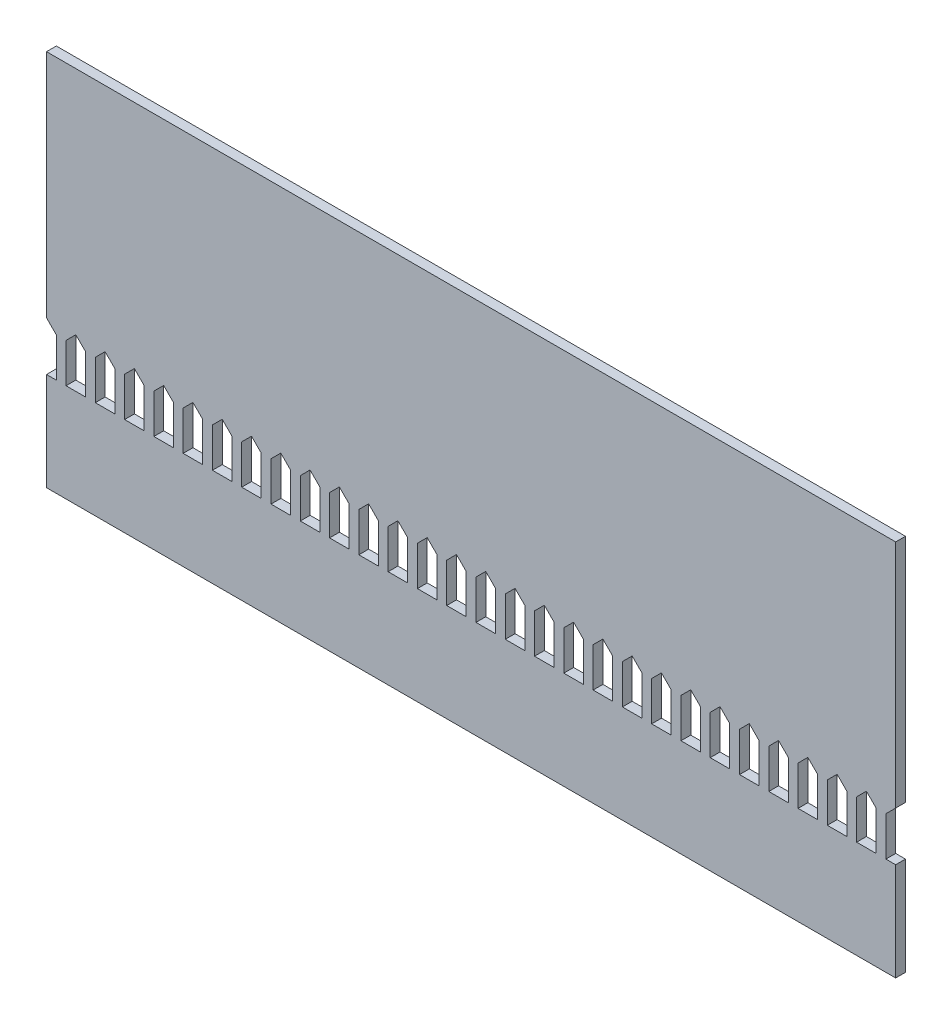
SolidWorks part; units mm, degrees
ref_plane "Front Plane" through (0, 0, 0) normal (0, 0, 1) x (1, 0, 0)
ref_plane "Top Plane" through (0, 0, 0) normal (0, 1, 0) x (1, 0, 0)
ref_plane "Right Plane" through (0, 0, 0) normal (1, 0, 0) x (0, 0, -1)
sketch "Sketch1" plane through (0, 0, 0) normal (0, 0, -1) x (1, 0, 0)
  line L1 (0, 0) -> (173.13, 0)
  line L3 (0, -47) -> (173.13, -47)
  line L5 (0, 30) -> (173.13, 30)
  line L7 (0, 0) -> (1.99, 1.99)
  line L8 (1.99, 1.99) -> (1.99, 10)
  line L9 (1.99, 10) -> (0, 10)
  line L10 (1.99, 5.995) -> (3.98, 5.995) construction
  line L11 (3.98, 1.99) -> (3.98, 10)
  line L12 (3.98, 1.99) -> (5.97, 0)
  line L13 (5.97, 0) -> (7.96, 1.99)
  line L14 (7.96, 1.99) -> (7.96, 10)
  line L15 (7.96, 10) -> (3.98, 10)
  line L16 (7.96, 1.99) -> (3.98, 1.99) construction
  line L17 (5.97, 0) -> (5.97, 1.99) construction
  line L23 (9.95, 1.99) -> (9.95, 10)
  line L44 (9.95, 1.99) -> (11.94, 0)
  line L65 (11.94, 0) -> (13.93, 1.99)
  line L86 (13.93, 1.99) -> (13.93, 10)
  line L107 (13.93, 10) -> (9.95, 10)
  line L128 (13.93, 1.99) -> (9.95, 1.99) construction
  line L149 (11.94, 0) -> (11.94, 1.99) construction
  line L170 (15.92, 1.99) -> (15.92, 10)
  line L191 (15.92, 1.99) -> (17.91, 0)
  line L207 (17.91, 0) -> (19.9, 1.99)
  line L213 (19.9, 1.99) -> (19.9, 10)
  line L219 (19.9, 10) -> (15.92, 10)
  line L225 (19.9, 1.99) -> (15.92, 1.99) construction
  line L231 (17.91, 0) -> (17.91, 1.99) construction
  line L237 (21.89, 1.99) -> (21.89, 10)
  line L243 (21.89, 1.99) -> (23.88, 0)
  line L249 (23.88, 0) -> (25.87, 1.99)
  line L255 (25.87, 1.99) -> (25.87, 10)
  line L261 (25.87, 10) -> (21.89, 10)
  line L267 (25.87, 1.99) -> (21.89, 1.99) construction
  line L273 (23.88, 0) -> (23.88, 1.99) construction
  line L279 (27.86, 1.99) -> (27.86, 10)
  line L285 (27.86, 1.99) -> (29.85, 0)
  line L291 (29.85, 0) -> (31.84, 1.99)
  line L297 (31.84, 1.99) -> (31.84, 10)
  line L303 (31.84, 10) -> (27.86, 10)
  line L309 (31.84, 1.99) -> (27.86, 1.99) construction
  line L315 (29.85, 0) -> (29.85, 1.99) construction
  line L316 (33.83, 1.99) -> (33.83, 10)
  line L317 (33.83, 1.99) -> (35.82, 0)
  line L318 (35.82, 0) -> (37.81, 1.99)
  line L319 (37.81, 1.99) -> (37.81, 10)
  line L320 (37.81, 10) -> (33.83, 10)
  line L321 (37.81, 1.99) -> (33.83, 1.99) construction
  line L322 (35.82, 0) -> (35.82, 1.99) construction
  line L323 (39.8, 1.99) -> (39.8, 10)
  line L324 (39.8, 1.99) -> (41.79, 0)
  line L325 (41.79, 0) -> (43.78, 1.99)
  line L326 (43.78, 1.99) -> (43.78, 10)
  line L327 (43.78, 10) -> (39.8, 10)
  line L328 (43.78, 1.99) -> (39.8, 1.99) construction
  line L329 (41.79, 0) -> (41.79, 1.99) construction
  line L330 (45.77, 1.99) -> (45.77, 10)
  line L331 (45.77, 1.99) -> (47.76, 0)
  line L332 (47.76, 0) -> (49.75, 1.99)
  line L333 (49.75, 1.99) -> (49.75, 10)
  line L334 (49.75, 10) -> (45.77, 10)
  line L335 (49.75, 1.99) -> (45.77, 1.99) construction
  line L336 (47.76, 0) -> (47.76, 1.99) construction
  line L337 (51.74, 1.99) -> (51.74, 10)
  line L338 (51.74, 1.99) -> (53.73, 0)
  line L339 (53.73, 0) -> (55.72, 1.99)
  line L340 (55.72, 1.99) -> (55.72, 10)
  line L341 (55.72, 10) -> (51.74, 10)
  line L342 (55.72, 1.99) -> (51.74, 1.99) construction
  line L343 (53.73, 0) -> (53.73, 1.99) construction
  line L344 (57.71, 1.99) -> (57.71, 10)
  line L345 (57.71, 1.99) -> (59.7, 0)
  line L346 (59.7, 0) -> (61.69, 1.99)
  line L347 (61.69, 1.99) -> (61.69, 10)
  line L348 (61.69, 10) -> (57.71, 10)
  line L349 (61.69, 1.99) -> (57.71, 1.99) construction
  line L350 (59.7, 0) -> (59.7, 1.99) construction
  line L351 (63.68, 1.99) -> (63.68, 10)
  line L352 (63.68, 1.99) -> (65.67, 0)
  line L353 (65.67, 0) -> (67.66, 1.99)
  line L354 (67.66, 1.99) -> (67.66, 10)
  line L355 (67.66, 10) -> (63.68, 10)
  line L356 (67.66, 1.99) -> (63.68, 1.99) construction
  line L357 (65.67, 0) -> (65.67, 1.99) construction
  line L358 (69.65, 1.99) -> (69.65, 10)
  line L359 (69.65, 1.99) -> (71.64, 0)
  line L360 (71.64, 0) -> (73.63, 1.99)
  line L361 (73.63, 1.99) -> (73.63, 10)
  line L362 (73.63, 10) -> (69.65, 10)
  line L363 (73.63, 1.99) -> (69.65, 1.99) construction
  line L364 (71.64, 0) -> (71.64, 1.99) construction
  line L365 (75.62, 1.99) -> (75.62, 10)
  line L366 (75.62, 1.99) -> (77.61, 0)
  line L367 (77.61, 0) -> (79.6, 1.99)
  line L368 (79.6, 1.99) -> (79.6, 10)
  line L369 (79.6, 10) -> (75.62, 10)
  line L370 (79.6, 1.99) -> (75.62, 1.99) construction
  line L371 (77.61, 0) -> (77.61, 1.99) construction
  line L372 (81.59, 1.99) -> (81.59, 10)
  line L373 (81.59, 1.99) -> (83.58, 0)
  line L374 (83.58, 0) -> (85.57, 1.99)
  line L375 (85.57, 1.99) -> (85.57, 10)
  line L376 (85.57, 10) -> (81.59, 10)
  line L377 (85.57, 1.99) -> (81.59, 1.99) construction
  line L378 (83.58, 0) -> (83.58, 1.99) construction
  line L379 (87.56, 1.99) -> (87.56, 10)
  line L380 (87.56, 1.99) -> (89.55, 0)
  line L381 (89.55, 0) -> (91.54, 1.99)
  line L382 (91.54, 1.99) -> (91.54, 10)
  line L383 (91.54, 10) -> (87.56, 10)
  line L384 (91.54, 1.99) -> (87.56, 1.99) construction
  line L385 (89.55, 0) -> (89.55, 1.99) construction
  line L386 (93.53, 1.99) -> (93.53, 10)
  line L387 (93.53, 1.99) -> (95.52, 0)
  line L388 (95.52, 0) -> (97.51, 1.99)
  line L389 (97.51, 1.99) -> (97.51, 10)
  line L390 (97.51, 10) -> (93.53, 10)
  line L391 (97.51, 1.99) -> (93.53, 1.99) construction
  line L392 (95.52, 0) -> (95.52, 1.99) construction
  line L393 (99.5, 1.99) -> (99.5, 10)
  line L394 (99.5, 1.99) -> (101.49, 0)
  line L395 (101.49, 0) -> (103.48, 1.99)
  line L396 (103.48, 1.99) -> (103.48, 10)
  line L397 (103.48, 10) -> (99.5, 10)
  line L398 (103.48, 1.99) -> (99.5, 1.99) construction
  line L399 (101.49, 0) -> (101.49, 1.99) construction
  line L400 (105.47, 1.99) -> (105.47, 10)
  line L401 (105.47, 1.99) -> (107.46, 0)
  line L402 (107.46, 0) -> (109.45, 1.99)
  line L403 (109.45, 1.99) -> (109.45, 10)
  line L404 (109.45, 10) -> (105.47, 10)
  line L405 (109.45, 1.99) -> (105.47, 1.99) construction
  line L406 (107.46, 0) -> (107.46, 1.99) construction
  line L407 (111.44, 1.99) -> (111.44, 10)
  line L408 (111.44, 1.99) -> (113.43, 0)
  line L409 (113.43, 0) -> (115.42, 1.99)
  line L410 (115.42, 1.99) -> (115.42, 10)
  line L411 (115.42, 10) -> (111.44, 10)
  line L412 (115.42, 1.99) -> (111.44, 1.99) construction
  line L413 (113.43, 0) -> (113.43, 1.99) construction
  line L414 (117.41, 1.99) -> (117.41, 10)
  line L415 (117.41, 1.99) -> (119.4, 0)
  line L416 (119.4, 0) -> (121.39, 1.99)
  line L417 (121.39, 1.99) -> (121.39, 10)
  line L418 (121.39, 10) -> (117.41, 10)
  line L419 (121.39, 1.99) -> (117.41, 1.99) construction
  line L420 (119.4, 0) -> (119.4, 1.99) construction
  line L421 (123.38, 1.99) -> (123.38, 10)
  line L422 (123.38, 1.99) -> (125.37, 0)
  line L423 (125.37, 0) -> (127.36, 1.99)
  line L424 (127.36, 1.99) -> (127.36, 10)
  line L425 (127.36, 10) -> (123.38, 10)
  line L426 (127.36, 1.99) -> (123.38, 1.99) construction
  line L427 (125.37, 0) -> (125.37, 1.99) construction
  line L428 (129.35, 1.99) -> (129.35, 10)
  line L429 (129.35, 1.99) -> (131.34, 0)
  line L430 (131.34, 0) -> (133.33, 1.99)
  line L431 (133.33, 1.99) -> (133.33, 10)
  line L432 (133.33, 10) -> (129.35, 10)
  line L433 (133.33, 1.99) -> (129.35, 1.99) construction
  line L434 (131.34, 0) -> (131.34, 1.99) construction
  line L435 (135.32, 1.99) -> (135.32, 10)
  line L436 (135.32, 1.99) -> (137.31, 0)
  line L437 (137.31, 0) -> (139.3, 1.99)
  line L438 (139.3, 1.99) -> (139.3, 10)
  line L439 (139.3, 10) -> (135.32, 10)
  line L440 (139.3, 1.99) -> (135.32, 1.99) construction
  line L441 (137.31, 0) -> (137.31, 1.99) construction
  line L442 (141.29, 1.99) -> (141.29, 10)
  line L443 (141.29, 1.99) -> (143.28, 0)
  line L444 (143.28, 0) -> (145.27, 1.99)
  line L445 (145.27, 1.99) -> (145.27, 10)
  line L446 (145.27, 10) -> (141.29, 10)
  line L447 (145.27, 1.99) -> (141.29, 1.99) construction
  line L448 (143.28, 0) -> (143.28, 1.99) construction
  line L449 (147.26, 1.99) -> (147.26, 10)
  line L450 (147.26, 1.99) -> (149.25, 0)
  line L451 (149.25, 0) -> (151.24, 1.99)
  line L452 (151.24, 1.99) -> (151.24, 10)
  line L453 (151.24, 10) -> (147.26, 10)
  line L454 (151.24, 1.99) -> (147.26, 1.99) construction
  line L455 (149.25, 0) -> (149.25, 1.99) construction
  line L456 (153.23, 1.99) -> (153.23, 10)
  line L457 (153.23, 1.99) -> (155.22, 0)
  line L458 (155.22, 0) -> (157.21, 1.99)
  line L459 (157.21, 1.99) -> (157.21, 10)
  line L460 (157.21, 10) -> (153.23, 10)
  line L461 (157.21, 1.99) -> (153.23, 1.99) construction
  line L462 (155.22, 0) -> (155.22, 1.99) construction
  line L463 (159.2, 1.99) -> (159.2, 10)
  line L464 (159.2, 1.99) -> (161.19, 0)
  line L465 (161.19, 0) -> (163.18, 1.99)
  line L466 (163.18, 1.99) -> (163.18, 10)
  line L467 (163.18, 10) -> (159.2, 10)
  line L468 (163.18, 1.99) -> (159.2, 1.99) construction
  line L469 (161.19, 0) -> (161.19, 1.99) construction
  line L470 (165.17, 1.99) -> (165.17, 10)
  line L471 (165.17, 1.99) -> (167.16, 0)
  line L472 (167.16, 0) -> (169.15, 1.99)
  line L473 (169.15, 1.99) -> (169.15, 10)
  line L474 (169.15, 10) -> (165.17, 10)
  line L475 (169.15, 1.99) -> (165.17, 1.99) construction
  line L476 (167.16, 0) -> (167.16, 1.99) construction
  line L477 (86.565, 30) -> (86.565, -47) construction
  line L478 (173.13, 0) -> (171.14, 1.99)
  line L479 (171.14, 1.99) -> (171.14, 10)
  line L480 (171.14, 10) -> (173.13, 10)
  line L481 (3.98, 1.99) -> (9.95, 1.99) construction
  line L482 (0, -47) -> (0, 30)
  line L483 (173.13, -47) -> (173.13, 30)
  line L484 (0, 10) -> (0, 0)
  line L485 (173.13, 0) -> (173.13, 10)
  point P15 (3.98, 5.995)
  dimension "D1" = 173.13
  dimension "D2" = 47
  dimension "D4" = 10
  dimension "Width" = 1.99
  dimension "D7" = 1.99
  dimension "D6" = 3.98
  dimension "D8" = 5.97
  dimension "D9" = 30
  dimension "D3" = 45
  dimension "D5" = 28
extrude "Boss-Extrude1" add sketch "Sketch1" along normal blind 2 contours L483 L3 L482 L1 | L483 L480 L479 L478 L1 L472 L473 L474 L470 L471 L465 L466 L467 L463 L464 L458 L459 L460 L456 L457 L451 L452 L453 L449 L450 L444 L445 L446 L442 L443 L437 L438 L439 L435 L436 L430 L431 L432 L428 L429 L423 L424 L425 L421
equation "\"D7@Sketch1\"=\"Width@Sketch1\""
equation "\"D6@Sketch1\"=2*\"Width@Sketch1\""
